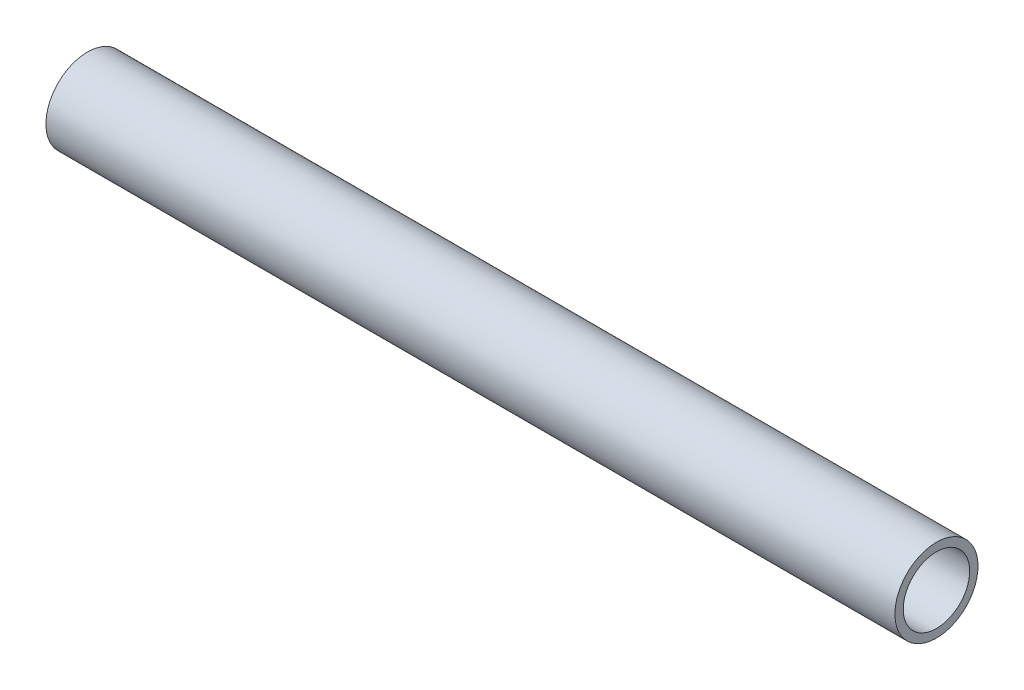
SolidWorks part; units mm, degrees
material "PC High Viscosity"
ref_plane "Front Plane" through (0, 0, 0) normal (0, 0, 1) x (1, 0, 0)
ref_plane "Top Plane" through (0, 0, 0) normal (0, 1, 0) x (1, 0, 0)
ref_plane "Right Plane" through (0, 0, 0) normal (1, 0, 0) x (0, 0, -1)
sketch "Sketch1" plane through (0, 0, 0) normal (1, 0, 0) x (0, 0, -1)
  circle A0 centre (0, 0) radius 15.875
  dimension "D1" = 31.75
extrude "Extrude-Thin1" add sketch "Sketch1" along normal mid plane 324.4865 thin thin type one direction reverse wall 3.175
